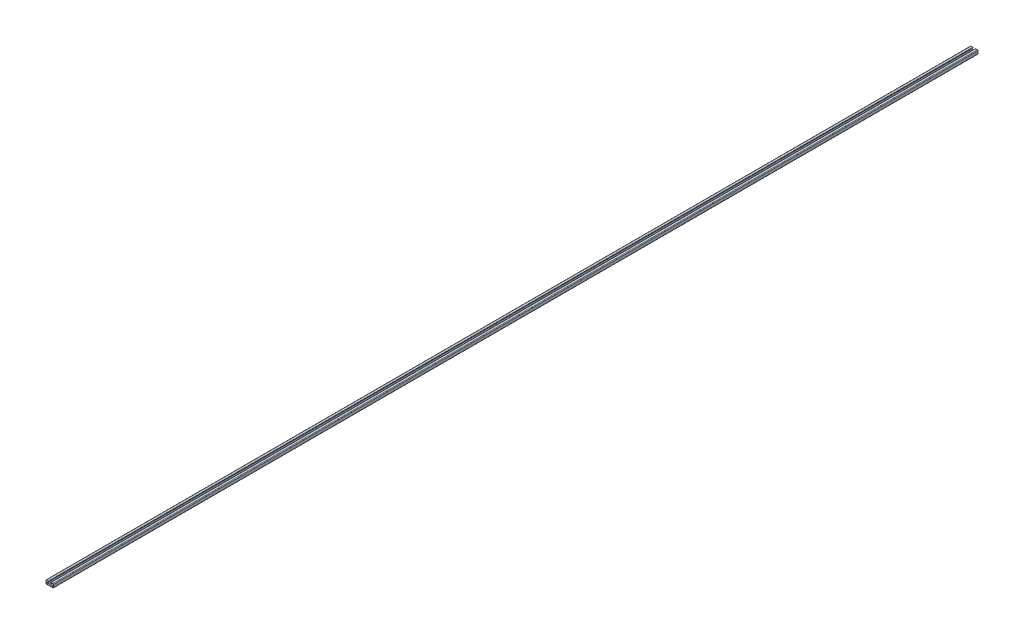
SolidWorks part; units mm, degrees
ref_plane "Front Plane" through (0, 0, 0) normal (0, 0, 1) x (1, 0, 0)
ref_plane "Top Plane" through (0, 0, 0) normal (0, 1, 0) x (1, 0, 0)
ref_plane "Right Plane" through (0, 0, 0) normal (1, 0, 0) x (0, 0, -1)
sketch "Sketch1" plane through (0, 0, 0) normal (0, 0, 1) x (1, 0, 0)
  line L5 (3.25, -1.87) -> (-3.25, -1.87)
  line L6 (12.5, 6.25) -> (-12.5, 6.25)
  line L10 (12.5, 6.25) -> (12.5, -6.25)
  line L11 (12.5, -6.25) -> (-12.5, -6.25)
  line L12 (-12.5, 6.25) -> (-12.5, -6.25)
  line L13 (12.5, 6.25) -> (-12.5, -6.25) construction
  line L14 (12.5, -6.25) -> (-12.5, 6.25) construction
  line L15 (7.345, 3.97) -> (-7.345, 3.97)
  line L16 (3.25, 6.25) -> (3.25, 3.97)
  line L17 (-3.25, 6.25) -> (-3.25, 3.97)
  line L18 (7.345, 3.97) -> (3.25, -1.87)
  line L19 (-3.25, -1.87) -> (-7.345, 3.97)
  circle A0 centre (-8.5, -2.25) radius 2
  circle A1 centre (8.5, -2.25) radius 2
  point P0 (0, 0)
  dimension "D3" = 4
  dimension "D4" = 4
  dimension "D1" = 25
  dimension "D2" = 12.5
  dimension "D5" = 4
  dimension "D6" = 4
  dimension "D7" = 17
  dimension "D8" = 6.5
  dimension "D9" = 14.69
  dimension "D10" = 6.5
  dimension "D11" = 9.25
  dimension "D12" = 5.155
  dimension "D13" = 9.25
  dimension "D14" = 5.84
  dimension "D15" = 8.12
extrude "Boss-Extrude2" add sketch "Sketch1" along normal blind 3048 contours L5 L19 L15 L17 L6 L12 L11 L10 L16 L18 A1 A0
fillet "Fillet1" radius 1.065 4 edges at (-3.25, 3.97, 1524) (-3.25, 6.25, 1524) (3.25, 3.97, 1524) (3.25, 6.25, 1524)
fillet "Fillet4" radius 2.13 1 edges at (12.5, 6.25, 1524)
fillet "Fillet5" radius 2.13 3 edges at (12.5, -6.25, 1524) (-12.5, -6.25, 1524) (-12.5, 6.25, 1524)
fillet "Fillet8" radius 0.5325 1 edges at (7.345, 3.97, 1524)
fillet "Fillet11" radius 0.5325 1 edges at (-7.345, 3.97, 1524)
fillet "Fillet15" radius 3 1 edges at (-3.25, -1.87, 1524)
fillet "Fillet16" radius 3 1 edges at (3.25, -1.87, 1524)
